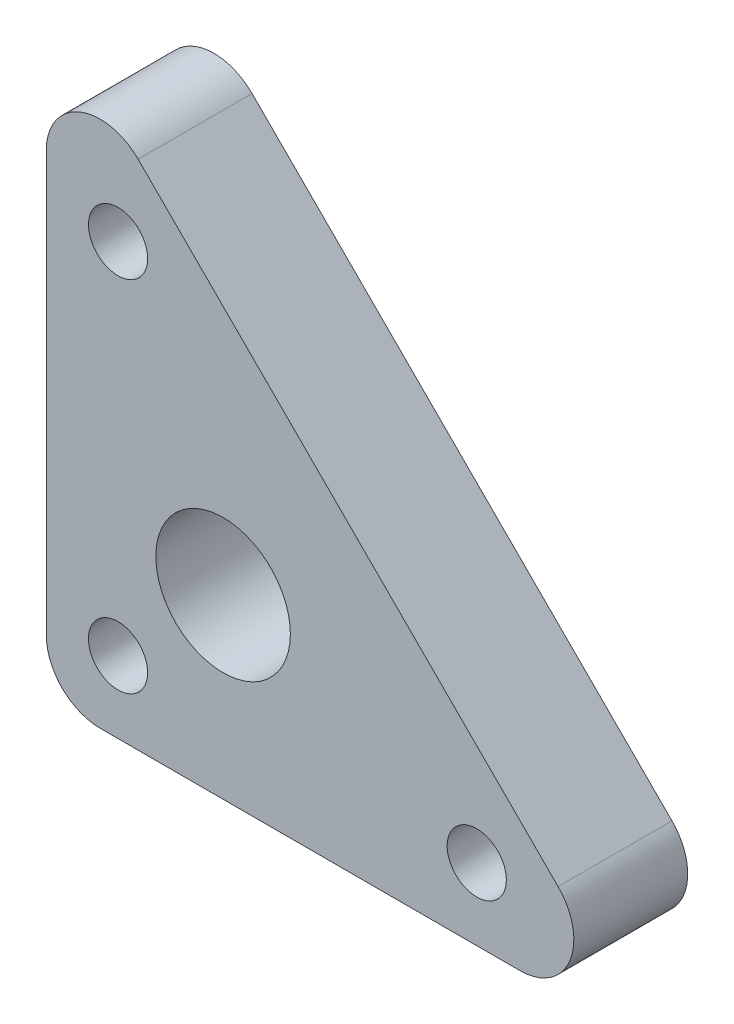
SolidWorks part; units mm, degrees
material "Balsa"
ref_plane "Front Plane" through (0, 0, 0) normal (0, 0, 1) x (1, 0, 0)
ref_plane "Top Plane" through (0, 0, 0) normal (0, 1, 0) x (1, 0, 0)
ref_plane "Right Plane" through (0, 0, 0) normal (1, 0, 0) x (0, 0, -1)
sketch "Sketch1" plane through (0, 0, 0) normal (0, 0, 1) x (1, 0, 0)
  line L0 (0, 0) -> (0, 20) construction
  line L1 (0, 20) -> (20, 0) construction
  line L2 (20, 0) -> (0, 0) construction
  line L3 (-4, 29.6569) -> (29.6569, -4)
  line L4 (29.6569, -4) -> (-4, -4)
  line L5 (-4, -4) -> (-4, 29.6569)
  line L6 (0, 20) -> (5.8579, 5.8579) construction
  line L7 (5.8579, 5.8579) -> (20, 0) construction
  circle A0 centre (0, 20) radius 1.65
  circle A1 centre (20, 0) radius 1.65
  circle A2 centre (0, 0) radius 1.65
  circle A3 centre (5.8579, 5.8579) radius 3.75
  dimension "D4" = 3.3
  dimension "D5" = 7.5
  dimension "D1" = 20
  dimension "D2" = 20
  dimension "D6" = 22.5
  dimension "D3" = 4
extrude "Boss-Extrude1" add sketch "Sketch1" along normal blind 6.35
fillet "Fillet1" radius 3 3 edges at (-4, -4, 3.175) (29.6569, -4, 3.175) (-4, 29.6569, 3.175)
